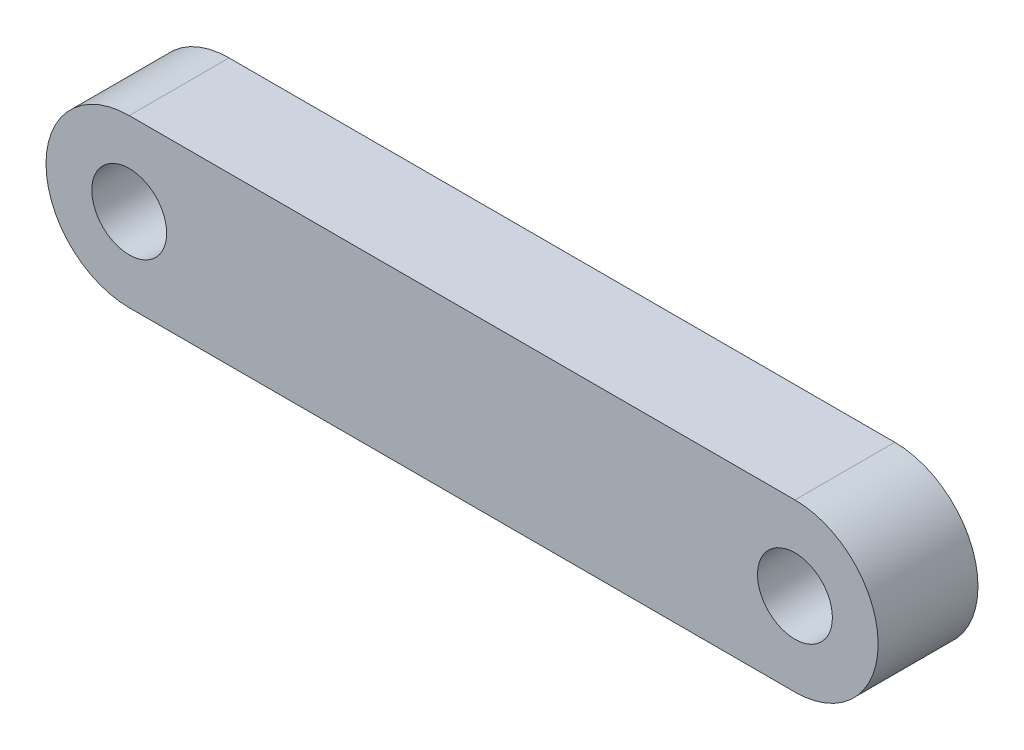
SolidWorks part; units mm, degrees
ref_plane "Спереди" through (0, 0, 0) normal (0, 0, 1) x (1, 0, 0)
ref_plane "Сверху" through (0, 0, 0) normal (0, 1, 0) x (1, 0, 0)
ref_plane "Справа" through (0, 0, 0) normal (1, 0, 0) x (0, 0, -1)
sketch "Эскиз1" plane through (0, 0, 0) normal (0, 0, 1) x (1, 0, 0)
  line L0 (0, 0) -> (40, 0) construction
  line L1 (0, 5) -> (40, 5)
  line L2 (0, -5) -> (40, -5)
  arc A0 (0, 5) -> (0, -5) centre (0, 0) ccw
  arc A1 (40, -5) -> (40, 5) centre (40, 0) ccw
  circle A2 centre (0, 0) radius 2.25
  circle A3 centre (40, 0) radius 2.25
  point P2 (20, 0)
  dimension "D3" = 4.5
  dimension "D1" = 40
  dimension "D2" = 10
extrude "Бобышка-Вытянуть1" add sketch "Эскиз1" along normal blind 6
